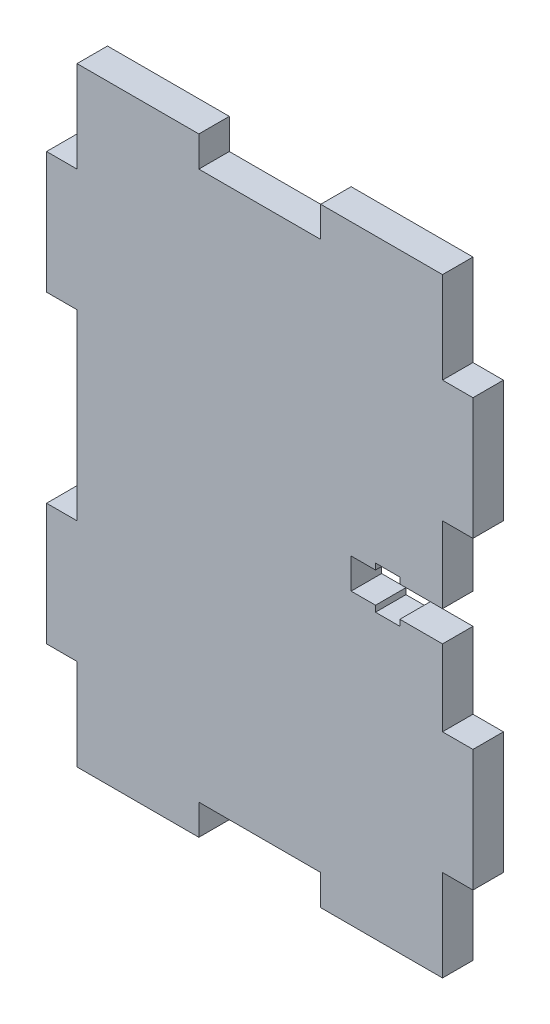
SolidWorks part; units mm, degrees
ref_plane "Plan de face" through (0, 0, 0) normal (0, 0, 1) x (1, 0, 0)
ref_plane "Plan de dessus" through (0, 0, 0) normal (0, 1, 0) x (1, 0, 0)
ref_plane "Plan de droite" through (0, 0, 0) normal (1, 0, 0) x (0, 0, -1)
sketch "Esquisse1" plane through (0, 0, 0) normal (0, 0, 1) x (1, 0, 0)
  line L0 (12.8824, 41.5) -> (32.8824, 41.5)
  line L1 (32.8824, 41.5) -> (32.8824, 46.5)
  line L2 (32.8824, 46.5) -> (52.8824, 46.5)
  line L3 (52.8824, 46.5) -> (52.8824, 31.5)
  line L4 (52.8824, 31.5) -> (57.8824, 31.5)
  line L5 (57.8824, 31.5) -> (57.8824, 11.5)
  line L6 (57.8824, 11.5) -> (52.8824, 11.5)
  line L7 (52.8824, 11.5) -> (52.8824, -1)
  line L8 (52.8824, -1) -> (45.8824, -1)
  line L9 (45.8824, -1) -> (45.8824, 0)
  line L10 (45.8824, 0) -> (41.8824, 0)
  line L11 (41.8824, 0) -> (41.8824, -1)
  line L12 (41.8824, -1) -> (37.8824, -1)
  line L13 (37.8824, -1) -> (37.8824, -6)
  line L14 (22.8824, 41.5) -> (22.8824, -3.5) construction
  line L15 (22.8824, -3.5) -> (37.8824, -3.5) construction
  line L16 (-12.1176, 11.5) -> (-7.1176, 11.5)
  line L17 (-12.1176, 31.5) -> (-12.1176, 11.5)
  line L18 (-7.1176, 31.5) -> (-12.1176, 31.5)
  line L19 (-7.1176, 46.5) -> (-7.1176, 31.5)
  line L20 (12.8824, 46.5) -> (-7.1176, 46.5)
  line L21 (12.8824, 41.5) -> (12.8824, 46.5)
  line L22 (12.8824, -48.5) -> (12.8824, -53.5)
  line L23 (12.8824, -53.5) -> (-7.1176, -53.5)
  line L24 (-7.1176, -53.5) -> (-7.1176, -38.5)
  line L25 (-7.1176, -38.5) -> (-12.1176, -38.5)
  line L26 (-12.1176, -38.5) -> (-12.1176, -18.5)
  line L27 (-12.1176, -18.5) -> (-7.1176, -18.5)
  line L28 (41.8824, -6) -> (37.8824, -6)
  line L29 (41.8824, -7) -> (41.8824, -6)
  line L30 (45.8824, -7) -> (41.8824, -7)
  line L31 (45.8824, -6) -> (45.8824, -7)
  line L32 (52.8824, -6) -> (45.8824, -6)
  line L33 (52.8824, -18.5) -> (52.8824, -6)
  line L34 (57.8824, -18.5) -> (52.8824, -18.5)
  line L35 (57.8824, -38.5) -> (57.8824, -18.5)
  line L36 (52.8824, -38.5) -> (57.8824, -38.5)
  line L37 (52.8824, -53.5) -> (52.8824, -38.5)
  line L38 (32.8824, -53.5) -> (52.8824, -53.5)
  line L39 (32.8824, -48.5) -> (32.8824, -53.5)
  line L40 (12.8824, -48.5) -> (32.8824, -48.5)
  line L41 (-7.1176, 11.5) -> (-7.1176, -18.5)
  dimension "D1" = 15
  dimension "D2" = 5
  dimension "D3" = 20
  dimension "D4" = 12.5
  dimension "D5" = 7
  dimension "D6" = 4
  dimension "D7" = 4
  dimension "D8" = 1
  dimension "D9" = 2.5
  dimension "D10" = 20
  dimension "D11" = 5
  dimension "D12" = 30
extrude "Boss.-Extru.1" add sketch "Esquisse1" along normal blind 5
